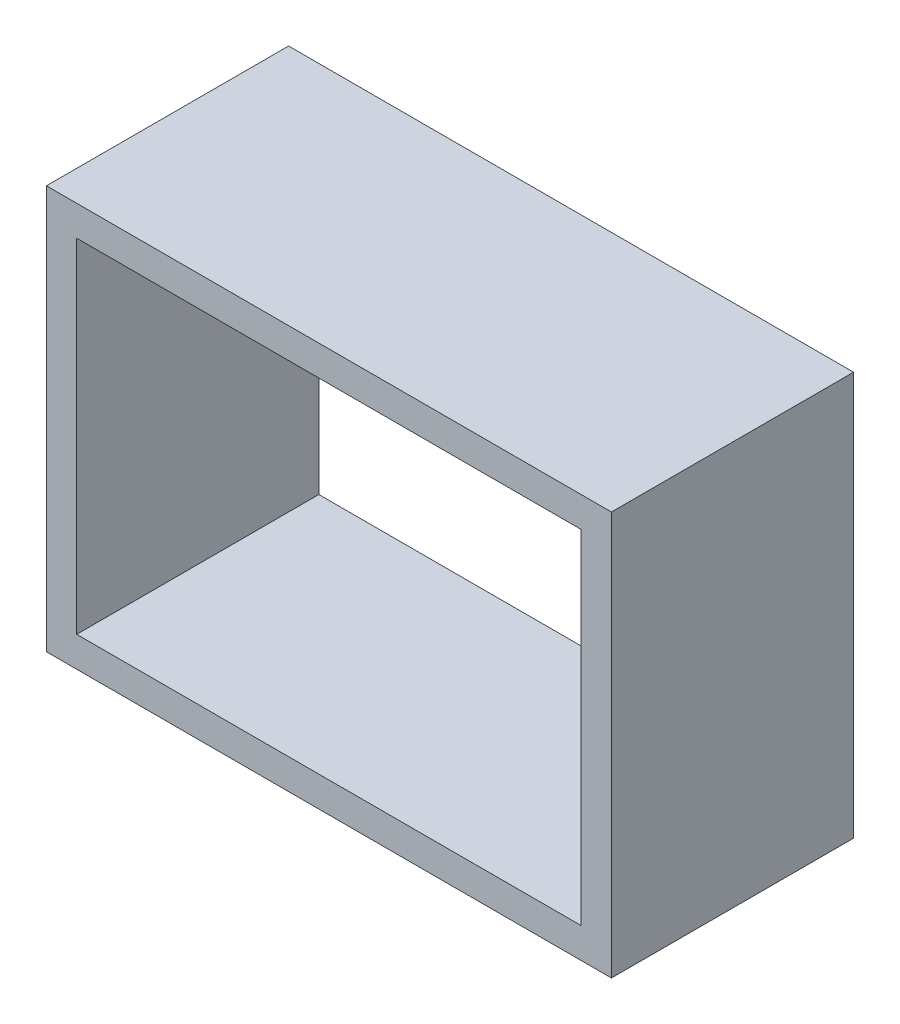
SolidWorks part; units mm, degrees
ref_plane "前视基准面" through (0, 0, 0) normal (0, 0, 1) x (1, 0, 0)
ref_plane "上视基准面" through (0, 0, 0) normal (0, 1, 0) x (1, 0, 0)
ref_plane "右视基准面" through (0, 0, 0) normal (1, 0, 0) x (0, 0, -1)
sketch "草图1" plane through (0, 0, 0) normal (0, 0, 1) x (1, 0, 0)
  line L1 (0, 0) -> (280, 0)
  line L2 (0, 0) -> (0, -200)
  line L3 (0, -200) -> (280, -200)
  line L4 (280, 0) -> (280, -200)
  dimension "D1" = 280
  dimension "D2" = 200
extrude "凸台-拉伸1" add sketch "草图1" along normal blind 120
sketch "草图2" plane through (0, 0, 0) normal (0, 0, -1) x (-1, 0, 0)
  line L0 (-280, 0) -> (0, 0) construction
  line L1 (-265, -15) -> (-15, -15)
  line L2 (-265, -15) -> (-265, -185)
  line L3 (-265, -185) -> (-15, -185)
  line L4 (-15, -15) -> (-15, -185)
  line L6 (-280, -200) -> (-280, 0) construction
  dimension "D1" = 170
  dimension "D2" = 15
  dimension "D3" = 15
  dimension "D4" = 250
extrude "切除-拉伸1" cut sketch "草图2" against normal blind 120
